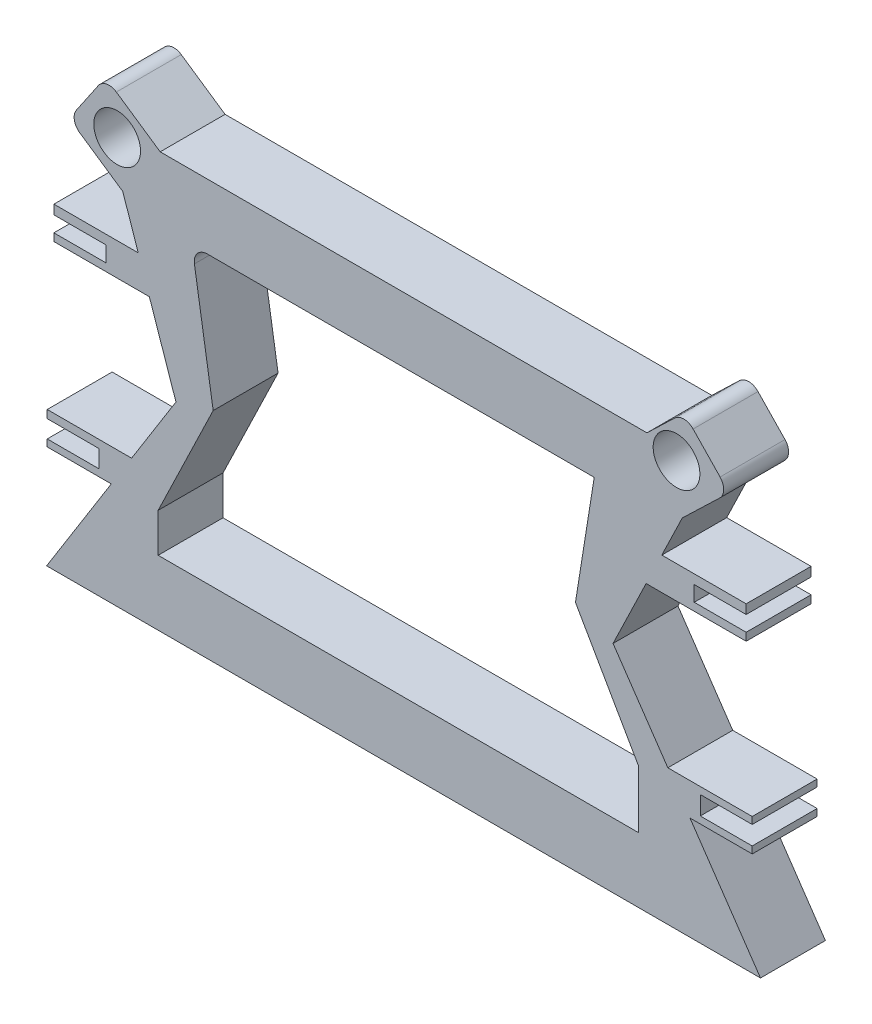
SolidWorks part; units mm, degrees
ref_plane "Front Plane" through (0, 0, 0) normal (0, 0, 1) x (1, 0, 0)
ref_plane "Top Plane" through (0, 0, 0) normal (0, 1, 0) x (1, 0, 0)
ref_plane "Right Plane" through (0, 0, 0) normal (1, 0, 0) x (0, 0, -1)
sketch "Sketch1" plane through (0, 0, 0) normal (0, 0, 1) x (1, 0, 0)
  line L0 (-24.5264, 99.1632) -> (350.4736, 99.1632)
  line L1 (350.4736, 99.1632) -> (371.9148, 119.7764)
  line L2 (386.0542, 119.498) -> (406.8457, 97.8714)
  line L3 (406.5673, 83.732) -> (377.7318, 56.0099)
  line L4 (437.9736, -220.8368) -> (324.3812, -54.4146)
  line L5 (324.3812, -54.4146) -> (377.7318, 56.0099)
  line L6 (437.9736, -220.8368) -> (-112.0264, -220.8368)
  line L7 (-112.0264, -220.8368) -> (-12.3713, -61.6866)
  line L8 (-12.3713, -61.6866) -> (-53.3713, 58.3134)
  line L9 (-53.3713, 58.3134) -> (-86.435, 80.8254)
  line L10 (-89.073, 94.7193) -> (-72.189, 119.5171)
  line L11 (-58.2951, 122.1551) -> (-24.5264, 99.1632)
  line L12 (11.7209, 49.1632) -> (309.884, 49.1632)
  line L13 (309.884, 49.1632) -> (295.4279, -41.4933)
  line L14 (295.4279, -41.4933) -> (343.869, -126.0826)
  line L15 (343.869, -126.0826) -> (343.869, -170.8368)
  line L16 (343.869, -170.8368) -> (-26.1037, -170.8368)
  line L17 (-26.1037, -170.8368) -> (-26.1037, -140.8385)
  line L18 (-26.1037, -140.8385) -> (16.3018, -53.068)
  line L19 (16.3018, -53.068) -> (1.8457, 37.5885)
  arc A0 (406.8457, 97.8714) -> (406.5673, 83.732) centre (399.6368, 90.9409) cw
  arc A1 (371.9148, 119.7764) -> (386.0542, 119.498) centre (378.8453, 112.5675) cw
  arc A2 (-86.435, 80.8254) -> (-89.073, 94.7193) centre (-80.807, 89.0913) cw
  arc A3 (-72.189, 119.5171) -> (-58.2951, 122.1551) centre (-63.9231, 113.8891) cw
  arc A4 (11.7209, 49.1632) -> (1.8457, 37.5885) centre (11.7209, 39.1632) ccw
  point P13 (162.9736, 99.1632)
  point P15 (162.9736, -220.8368)
  point P22 (16.3018, -65.1287)
  point P23 (-4.901, -61.6866)
  point P24 (0, 40.5446)
  point P27 (413.7762, 90.6625)
  point P30 (379.1237, 126.7069)
  point P33 (-94.701, 86.4534)
  point P36 (-66.561, 127.7831)
  dimension "D9" = 10
  dimension "D1" = 50
  dimension "D2" = 50
  dimension "D3" = 50
  dimension "D4" = 50
  dimension "D5" = 320
  dimension "D6" = 550
  dimension "D7" = 120
  dimension "D8" = 375
  dimension "D10" = 50
  dimension "D11" = 50
extrude "Boss-Extrude1" add sketch "Sketch1" along normal blind 50
sketch "Sketch2" plane through (0, 0, 50) normal (0, 0, 1) x (1, 0, 0)
  circle A0 centre (-57.6739, 92.0717) radius 18
  circle A1 centre (373.2808, 92.0717) radius 18
  dimension "D1" = 36
  dimension "D2" = 36
extrude "Cut-Extrude1" cut sketch "Sketch2" against normal blind 50
sketch "Sketch3" plane through (0, 0, 50) normal (0, 0, 1) x (1, 0, 0)
  line L0 (-41.4129, 23.3134) -> (-106.4129, 23.3134)
  line L1 (-53.3713, 58.3134) -> (-12.3713, -61.6866) construction
  line L2 (-106.4129, 23.3134) -> (-106.4129, -1.6866)
  line L3 (-106.4129, -1.6866) -> (-32.8713, -1.6866)
  line L4 (-46.5446, -116.2617) -> (-111.5446, -116.2617)
  line L5 (-12.3713, -61.6866) -> (-112.0264, -220.8368) construction
  line L6 (-111.5446, -116.2617) -> (-111.5446, -141.2617)
  line L7 (-111.5446, -141.2617) -> (-62.1989, -141.2617)
  line L8 (361.9348, 23.3134) -> (426.9348, 23.3134)
  line L9 (324.3812, -54.4146) -> (377.7318, 56.0099) construction
  line L10 (426.9348, 23.3134) -> (426.9348, -1.6866)
  line L11 (426.9348, -1.6866) -> (349.8563, -1.6866)
  line L12 (366.5953, -116.2617) -> (431.5953, -116.2617)
  line L13 (437.9736, -220.8368) -> (324.3812, -54.4146) construction
  line L14 (431.5953, -116.2617) -> (431.5953, -141.2617)
  line L15 (431.5953, -141.2617) -> (383.6592, -141.2617)
  line L16 (-41.4129, 23.3134) -> (-32.8713, -1.6866)
  line L17 (-46.5446, -116.2617) -> (-62.1989, -141.2617)
  line L18 (361.9348, 23.3134) -> (349.8563, -1.6866)
  line L19 (349.8563, -1.6866) -> (351.2307, -4.3129)
  line L20 (366.5953, -116.2617) -> (383.6592, -141.2617)
  dimension "D1" = 65
  dimension "D2" = 65
  dimension "D3" = 65
  dimension "D4" = 65
  dimension "D5" = 25
  dimension "D6" = 25
  dimension "D7" = 25
  dimension "D8" = 25
extrude "Boss-Extrude2" add sketch "Sketch3" against normal blind 50
sketch "Sketch4" plane through (0, 0, 50) normal (0, 0, 1) x (1, 0, 0)
  line L0 (-106.4129, 23.3134) -> (-106.4129, -1.6866) construction
  line L1 (-66.4129, 4.1717) -> (-106.4129, 4.1717)
  line L2 (-66.4129, 4.1717) -> (-66.4129, 16.1717)
  line L3 (-66.4129, 16.1717) -> (-106.4129, 16.1717)
  line L4 (-106.4129, 4.1717) -> (-106.4129, 16.1717)
  line L5 (-66.4129, 4.1717) -> (-106.4129, 16.1717) construction
  line L6 (-66.4129, 16.1717) -> (-106.4129, 4.1717) construction
  line L7 (-111.5446, -116.2617) -> (-111.5446, -141.2617) construction
  line L8 (-71.5446, -135.916) -> (-111.5446, -135.916)
  line L9 (-71.5446, -135.916) -> (-71.5446, -122.3971)
  line L10 (-71.5446, -122.3971) -> (-111.5446, -122.3971)
  line L11 (-111.5446, -135.916) -> (-111.5446, -122.3971)
  line L12 (-71.5446, -135.916) -> (-111.5446, -122.3971) construction
  line L13 (-71.5446, -122.3971) -> (-111.5446, -135.916) construction
  line L14 (431.5953, -116.2617) -> (431.5953, -141.2617) construction
  line L15 (391.5953, -121.6074) -> (431.5953, -121.6074)
  line L16 (391.5953, -121.6074) -> (391.5953, -135.916)
  line L17 (391.5953, -135.916) -> (431.5953, -135.916)
  line L18 (431.5953, -121.6074) -> (431.5953, -135.916)
  line L19 (391.5953, -121.6074) -> (431.5953, -135.916) construction
  line L20 (391.5953, -135.916) -> (431.5953, -121.6074) construction
  line L21 (426.9348, 23.3134) -> (426.9348, -1.6866) construction
  line L22 (386.9348, 16.1717) -> (426.9348, 16.1717)
  line L23 (386.9348, 16.1717) -> (386.9348, 4.3426)
  line L24 (386.9348, 4.3426) -> (426.9348, 4.3426)
  line L25 (426.9348, 16.1717) -> (426.9348, 4.3426)
  line L26 (386.9348, 16.1717) -> (426.9348, 4.3426) construction
  line L27 (386.9348, 4.3426) -> (426.9348, 16.1717) construction
  point P0 (-86.4129, 10.1717)
  point P7 (-91.5446, -129.1565)
  point P14 (411.5953, -128.7617)
  point P21 (406.9348, 10.2571)
  dimension "D1" = 40
  dimension "D2" = 12
  dimension "D3" = 40
  dimension "D4" = 11.829
extrude "Cut-Extrude2" cut sketch "Sketch4" against normal blind 50
